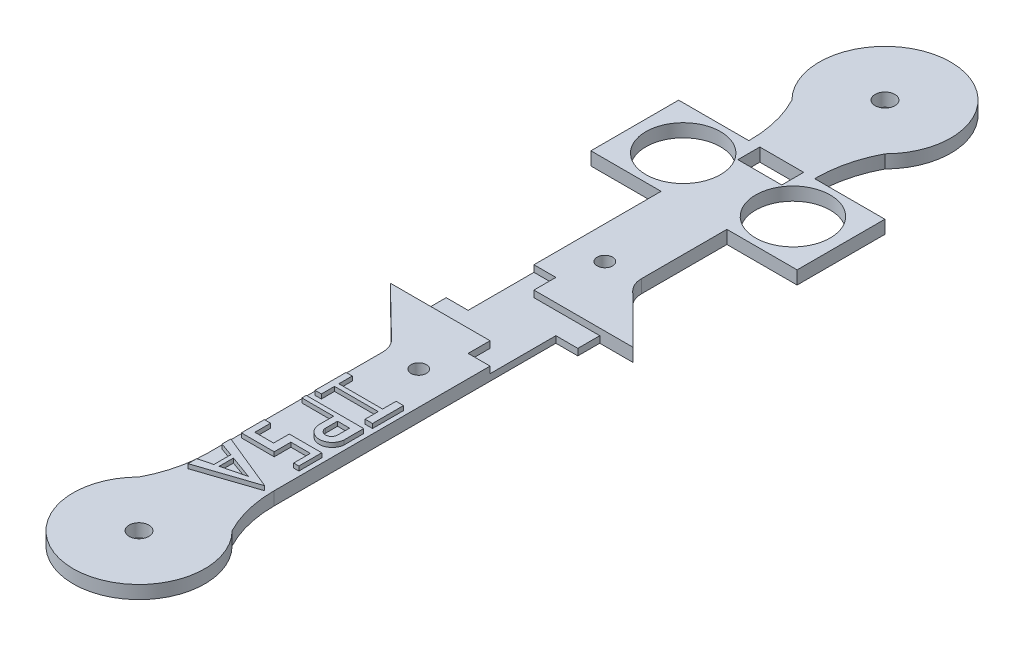
SolidWorks part; units mm, degrees
material "ABS"
ref_plane "Front Plane" through (0, 0, 0) normal (0, 0, 1) x (1, 0, 0)
ref_plane "Top Plane" through (0, 0, 0) normal (0, 1, 0) x (1, 0, 0)
ref_plane "Right Plane" through (0, 0, 0) normal (1, 0, 0) x (0, 0, -1)
sketch "Sketch1" plane through (0, 0, 0) normal (0, 1, 0) x (1, 0, 0)
  line L0 (-19.3064, 0) -> (26.0375, 0) construction
  line L3 (-7.451, -61.7809) -> (-7.451, 61.7809)
  line L4 (7.549, -61.7809) -> (7.549, 61.7809)
  arc A6 (10.6556, 74.3934) -> (-10.5576, 74.3934) centre (0.049, 85) ccw
  arc A12 (-7.451, 61.7809) -> (-10.5576, 74.3934) centre (-34.607, 61.7809) ccw
  arc A13 (7.549, 61.7809) -> (10.6556, 74.3934) centre (34.705, 61.7809) cw
  circle A14 centre (0.049, 85) radius 2
  circle A27 centre (0, 20) radius 1.5
  circle A30 centre (0.049, -85) radius 2
  arc A33 (7.549, -61.7809) -> (10.6556, -74.3934) centre (34.705, -61.7809) ccw
  arc A34 (10.6556, -74.3934) -> (-10.5576, -74.3934) centre (0.049, -85) cw
  arc A35 (-7.451, -61.7809) -> (-10.5576, -74.3934) centre (-34.607, -61.7809) cw
  circle A36 centre (0, -20) radius 1.5
  point P41 (7.549, 0)
  point P42 (-7.451, 0)
  dimension "D2" = 4
  dimension "D7" = 4
  dimension "D9" = 3
  dimension "D8" = 15
  dimension "D12" = 20
  dimension "D13" = 20
  dimension "D14" = 170
extrude "Boss-Extrude2" add sketch "Sketch1" along normal blind 3
sketch "Sketch3" plane through (0, 3, 0) normal (0, 1, 0) x (1, 0, 0)
  line L0 (-47.0006, 0) -> (46.456, 0) construction
  line L1 (7.549, -61.7809) -> (7.549, 61.7809) construction
  line L2 (-7.549, -7.5) -> (7.549, -7.5)
  line L3 (-7.549, -7.5) -> (-7.549, 7.5)
  line L4 (-7.549, 7.5) -> (7.549, 7.5)
  line L5 (7.549, -7.5) -> (7.549, 7.5)
  line L6 (-7.549, -7.5) -> (7.549, 7.5) construction
  line L7 (-7.549, 7.5) -> (7.549, -7.5) construction
  point P3 (0, 0)
  dimension "D1" = 15
extrude "Cut-Extrude9" cut sketch "Sketch3" against normal blind 1.5
sketch "Sketch4" plane through (0, 1.5, 0) normal (0, 1, 0) x (1, 0, 0)
  line L1 (-7.451, -7.5) -> (-20.167, -7.5)
  line L2 (-7.451, -7.5) -> (-7.3802, -20)
  line L3 (-7.3802, -20) -> (-20.167, -7.5)
  line L9 (-20.167, -20) -> (-7.3802, -20)
  line L10 (-20.167, -20) -> (-20.167, -7.5)
  line L13 (-7.451, -7.5) -> (-20.167, -7.5)
  line L14 (-20.167, -7.5) -> (-7.451, -7.5)
  line L17 (-20.167, -20) -> (-13.8196, -13.7051) construction
  line L19 (7.549, -7.5) -> (7.549, 7.5) construction
  line L20 (7.549, 7.5) -> (-7.451, 7.5) construction
  line L21 (7.549, 7.5) -> (20.167, 7.5)
  line L24 (-7.5626, -7.5) -> (7.5626, 7.5) construction
  line L25 (7.549, 7.5) -> (7.549, 20)
  line L26 (7.549, 20) -> (20.167, 7.5)
  point P0 (0, 0)
  point P7 (0, 0)
extrude "Boss-Extrude7" add sketch "Sketch4" along normal mid plane 3 contours L3 L2 L1 | L26 L25 L21
sketch "Sketch5" plane through (0, 3, 0) normal (0, 1, 0) x (1, 0, 0)
  line L0 (7.549, 2.5) -> (7.549, 7.5)
  line L10 (-20.167, -7.5) -> (7.549, -7.5) construction
  line L19 (7.549, -61.7809) -> (7.549, -7.5) construction
  line L20 (20.167, 7.5) -> (-7.451, 7.5) construction
  line L21 (7.549, 7.5) -> (2.549, 7.5)
  line L22 (-7.451, -2.5) -> (-7.451, -7.5)
  line L23 (-7.451, -7.5) -> (7.549, -7.5)
  line L25 (7.549, -7.5) -> (5.2347, -7.5)
  line L33 (-7.451, -7.5) -> (-2.451, -7.5)
  line L37 (7.549, 7.5) -> (2.549, 7.5)
  line L41 (-7.451, -7.5) -> (-2.451, -7.5)
  line L42 (-7.451, -7.5) -> (-7.451, -2.5)
  line L43 (-7.451, -2.5) -> (-2.451, -2.5)
  line L44 (-2.451, -7.5) -> (-2.451, -2.5)
  line L45 (2.549, 7.5) -> (7.549, 7.5)
  line L46 (2.549, 7.5) -> (2.549, 2.5)
  line L47 (2.549, 2.5) -> (7.549, 2.5)
  line L48 (7.549, 7.5) -> (7.549, 2.5)
  line L50 (-7.451, -7.5) -> (-7.451, -2.5)
  line L53 (-7.451, -2.5) -> (-12.4461, -2.5)
  line L54 (-7.451, -2.5) -> (-7.451, -7.5)
  line L55 (-7.451, -7.5) -> (-12.4461, -7.5)
  line L56 (-12.4461, -2.5) -> (-12.4461, -7.5)
  line L57 (7.549, 7.5) -> (12.549, 7.5)
  line L58 (7.549, 7.5) -> (7.549, 2.5)
  line L59 (7.549, 2.5) -> (12.549, 2.5)
  line L60 (12.549, 7.5) -> (12.549, 2.5)
  dimension "D1" = 5
  dimension "D5" = 5
  dimension "D6" = 5
sketch "Sketch7" plane through (0, 3, 0) normal (0, 1, 0) x (1, 0, 0)
  line L0 (-7.451, -19.9308) -> (-8.8812, -18.5327)
  line L1 (7.549, 20) -> (7.549, 22)
  line L5 (-34.7561, 0) -> (40.5625, 0) construction
  line L6 (7.549, 20) -> (7.549, 61.7809) construction
  line L8 (7.549, 20) -> (20.167, 7.5) construction
  line L9 (8.9698, 18.5924) -> (7.549, 20)
  line L10 (-7.451, -19.9308) -> (-20.167, -7.5) construction
  line L11 (-7.451, -19.9308) -> (-7.451, -21.9308)
  line L12 (-7.451, -19.9308) -> (-7.451, -61.7809) construction
  arc A0 (-7.451, -21.9308) -> (-8.8812, -18.5327) centre (-12.203, -21.9308) ccw
  arc A1 (7.549, 22) -> (8.9698, 18.5924) centre (12.3455, 22) ccw
  dimension "D1" = 2
  dimension "D2" = 2
  dimension "D3" = 2
  dimension "D4" = 2
extrude "Boss-Extrude9" add sketch "Sketch7" against normal blind 3
sketch "Sketch11" plane through (0, 3, 0) normal (0, 1, 0) x (1, 0, 0)
  line L1 (-7.451, 7.5) -> (-2.451, 7.5)
  line L2 (-7.451, 7.5) -> (-7.451, 12.5)
  line L3 (-7.451, 12.5) -> (-2.451, 12.5)
  line L4 (-2.451, 7.5) -> (-2.451, 12.5)
  line L5 (7.549, -7.5) -> (2.549, -7.5)
  line L6 (7.549, -7.5) -> (7.549, -12.5)
  line L7 (7.549, -12.5) -> (2.549, -12.5)
  line L8 (2.549, -7.5) -> (2.549, -12.5)
  dimension "D1" = 5
  dimension "D2" = 5
  dimension "D3" = 5
  dimension "D4" = 5
extrude "Cut-Extrude16" cut sketch "Sketch11" against normal blind 1.5
sketch "Sketch12" plane through (0, 1.5, 0) normal (0, 1, 0) x (1, 0, 0)
  line L0 (7.549, 7.5) -> (-2.451, 7.5) construction
  line L1 (-7.451, -7.5) -> (-12.451, -7.5)
  line L2 (-7.451, -7.5) -> (-7.451, -2.5)
  line L3 (-7.451, -2.5) -> (-12.451, -2.5)
  line L4 (-12.451, -7.5) -> (-12.451, -2.5)
  line L5 (7.549, 7.5) -> (12.549, 7.5)
  line L6 (7.549, 7.5) -> (7.549, 2.5)
  line L7 (7.549, 2.5) -> (12.549, 2.5)
  line L8 (12.549, 7.5) -> (12.549, 2.5)
  line L9 (7.549, -12.5) -> (7.549, 7.5) construction
  dimension "D1" = 5
  dimension "D2" = 5
  dimension "D3" = 5
  dimension "D4" = 5
extrude "Boss-Extrude16" add sketch "Sketch12" against normal blind 1.5
sketch "Sketch15" plane through (0, 3, 0) normal (0, 1, 0) x (1, 0, 0)
  circle A0 centre (0, -20) radius 1.5
  circle A1 centre (0, 20) radius 1.5
extrude "Boss-Extrude17" add sketch "Sketch15" against normal blind 3
sketch "Sketch16" plane through (0, 3, 0) normal (0, 1, 0) x (1, 0, 0)
  line L1 (24.0526, 0) -> (-32.7174, 0) construction
  circle A0 centre (0, -21.2132) radius 1.5
  circle A1 centre (0, 21.2132) radius 1.5
  dimension "D1" = 3
  dimension "D2" = 3
  dimension "D3" = 42.4264
extrude "Cut-Extrude17" cut sketch "Sketch16" against normal through all
sketch "Sketch18" plane through (0, 3, 0) normal (0, 1, 0) x (1, 0, 0)
  line L1 (7.549, 31.647) -> (-7.451, 31.647)
  line L6 (-7.451, 31.647) -> (-7.451, 46.246)
  line L7 (0.049, 85) -> (0.049, 61.4736) construction
  line L10 (7.549, 31.647) -> (3.8438, 41.4736)
  line L12 (22.5624, 61.4736) -> (-22.4376, 61.4736)
  line L14 (22.5624, 41.4736) -> (-22.4376, 41.4736)
  line L17 (0, 0) -> (0.049, 85) construction
  line L18 (0.049, 41.4736) -> (0.049, 13.3789) construction
  line L19 (-22.4376, 41.4736) -> (-23.4509, 41.4736)
  line L20 (-23.4509, 41.4736) -> (-23.4509, 61.4736)
  line L21 (-23.4509, 61.4736) -> (-22.4376, 61.4736)
  line L22 (23.5491, 51.4736) -> (23.5491, 61.4736)
  line L23 (23.5491, 61.4736) -> (22.5624, 61.4736)
  line L24 (23.5491, 51.4736) -> (23.5491, 41.4736)
  line L25 (23.5491, 41.4736) -> (22.5624, 41.4736)
  line L26 (5.049, 61.4736) -> (5.049, 56.4736)
  line L27 (5.049, 56.4736) -> (-4.951, 56.4736)
  line L28 (7.549, 46.246) -> (7.549, 31.647)
  line L29 (4.0297, 51.5366) -> (12.5297, 51.5366) construction
  line L30 (23.5491, 61.4736) -> (-23.4509, 41.4736) construction
  line L31 (-3.9703, 51.5366) -> (-12.4703, 51.5366) construction
  line L32 (4.0297, 51.5366) -> (-3.9703, 51.5366) construction
  line L33 (0.049, 61.4736) -> (5.049, 61.4736)
  line L34 (0.049, 61.4736) -> (-4.951, 61.4736)
  line L35 (-4.951, 56.4736) -> (-4.951, 61.4736)
  line L36 (-4.951, 56.4736) -> (-4.4703, 56.4736)
  circle A0 centre (12.5297, 51.5366) radius 8.5
  circle A1 centre (-12.4703, 51.5366) radius 8.5
  point P6 (0.049, 51.5375)
  line M16 (7.549, 22) -> (7.549, 61.7809)
  line M20 (-7.451, 61.7809) -> (-7.451, 12.5)
  dimension "D5" = 8.5
  dimension "D6" = 5
  dimension "D1" = 4
  dimension "D2" = 20
  dimension "D3" = 4
  dimension "D4" = 8.5
  dimension "D7" = 5
sketch "Sketch23" plane through (0, 3, 0) normal (0, 1, 0) x (1, 0, 0)
  line L0 (4.7905, -31.1563) -> (4.7905, -34.2247)
  line L1 (-7.451, -21.9308) -> (7.4854, -21.9308)
  line L2 (-7.451, -21.9308) -> (-7.451, -82.5219)
  line L3 (-7.451, -82.5219) -> (7.4854, -82.5219)
  line L4 (7.4854, -21.9308) -> (7.4854, -82.5219)
  line L5 (-6.6102, -81.3428) -> (6.483, -81.3428)
  line L6 (-6.6102, -81.3428) -> (-6.6102, -31.1563)
  line L7 (-6.6102, -31.1563) -> (6.483, -31.1563)
  line L8 (6.483, -81.3428) -> (6.483, -31.1563)
  line L9 (4.7905, -34.2247) -> (-5.1932, -34.2247)
  line L10 (-5.1932, -34.2247) -> (-5.1932, -31.1563)
  line L11 (6.483, -38.2247) -> (4.7905, -38.2247)
  line L12 (4.7905, -35.2247) -> (4.7905, -38.2247)
  line L13 (4.7905, -35.2247) -> (-5.172, -35.2247)
  line L14 (-5.172, -35.2247) -> (-5.172, -38.2247)
  line L15 (-5.172, -38.2247) -> (-6.6102, -38.2247)
  line L16 (-6.6102, -40.2287) -> (0.614, -40.2287)
  line L17 (0.614, -40.2287) -> (6.483, -40.2287)
  line L18 (6.483, -40.2287) -> (6.483, -46.7946)
  line L19 (0.614, -41.2287) -> (0.614, -44.4723)
  line L20 (-6.6102, -41.2287) -> (0.614, -41.2287)
  line L21 (4.7905, -41.7559) -> (2.0489, -41.7559)
  line L22 (2.0489, -41.7559) -> (2.0489, -44.4723)
  line L23 (4.7905, -44.4723) -> (4.7905, -41.7559)
  line L24 (6.483, -54.1856) -> (6.483, -49.4842)
  line L25 (-6.6102, -49.787) -> (-5.1932, -49.787)
  line L26 (5.304, -55.0101) -> (6.483, -55.0101)
  line L27 (0.8671, -55.0101) -> (-6.6102, -55.0101)
  line L28 (-6.6102, -55.0101) -> (-6.6102, -48.3283)
  line L29 (-6.6102, -57.4179) -> (-6.6102, -59.4179)
  line L30 (-5.1932, -49.787) -> (-5.1932, -53.3578)
  line L31 (-5.1932, -53.3578) -> (-0.919, -53.3578)
  line L32 (-0.919, -53.3578) -> (-0.919, -49.787)
  line L33 (-0.919, -49.787) -> (3.6751, -49.787)
  line L34 (3.6751, -49.787) -> (5.304, -49.787)
  line L35 (5.304, -51.2093) -> (5.304, -55.0101)
  line L36 (-6.6102, -57.4179) -> (6.483, -62.7841)
  line L37 (0.8671, -51.2093) -> (5.304, -51.2093)
  line L38 (0.8671, -51.2093) -> (0.8671, -55.0101)
  line L39 (5.304, -49.787) -> (6.483, -49.787)
  line L40 (-6.6102, -67.1769) -> (-6.6102, -65.1769)
  line L41 (6.483, -62.7841) -> (-6.6102, -67.1769)
  line L42 (-6.6102, -67.1769) -> (-6.6102, -64.1456)
  line L43 (-6.6102, -59.4179) -> (-3.4958, -60.5424)
  line L44 (-6.6102, -65.1769) -> (-3.4958, -64.3922)
  line L45 (-2.5421, -60.8868) -> (-2.5421, -64.1519)
  line L46 (-3.4958, -60.5424) -> (-3.4958, -64.3922)
  line L47 (-2.5421, -60.8868) -> (2.7839, -62.8099)
  line L48 (-2.5421, -64.1519) -> (2.7839, -62.8099)
  arc A2 (0.614, -44.4723) -> (6.483, -44.7743) centre (3.5563, -44.4723) ccw
  arc A3 (2.0489, -44.4723) -> (4.7905, -44.4723) centre (3.4197, -44.4723) ccw
  point P7 (-0.0636, -56.3282)
  dimension "D1" = 3.0684
  dimension "D2" = 3
  dimension "D3" = 3
  dimension "D4" = 1
  dimension "D5" = 1
  dimension "D6" = 2
  dimension "D7" = 2
extrude "Boss-Extrude23" add sketch "Sketch23" along normal blind 1 contours L15 L14 L13 L12 L11 L8 L7 L0 L9 L10 L6 | L19 A2 L18 L17 L16 L6 L20 A3 L22 L21 L23 | L39 L34 L33 L32 L31 L30 L25 L6 L27 L38 L37 L35 L26 L8 | L43 L46 L44 L6 L41 L36 L48 L45 L47
extrude "Boss-Extrude27" add sketch "Sketch18" against normal blind 3 contours A0 L14 L25 L24 L22 L23 L12 M16 | A1 L12 L21 L20 L19 L14 L6 M20
sketch "Sketch27" plane through (0, 3, 0) normal (0, 1, 0) x (1, 0, 0)
  line L0 (7.549, 61.4736) -> (-7.451, 61.4736)
  line L1 (-7.451, 61.4736) -> (-23.4509, 61.4736) construction
  line L2 (0.049, 61.4736) -> (0.049, 41.4736)
  line L3 (0.049, 61.4736) -> (5.049, 61.4736)
  line L4 (0.049, 61.4736) -> (-4.951, 61.4736)
  line L5 (5.049, 61.4736) -> (5.049, 56.4736)
  line L6 (5.049, 56.4736) -> (-4.951, 56.4736)
  line L7 (-4.951, 56.4736) -> (-4.951, 61.4736)
  circle A0 centre (12.5297, 51.5366) radius 8.5
  circle A1 centre (-12.4703, 51.5366) radius 8.5
  line M27 (7.549, 44.6488) -> (7.549, 58.4245)
  line M29 (-7.451, 58.3964) -> (-7.451, 44.6768)
  dimension "D1" = 5
  dimension "D2" = 5
  dimension "D3" = 5
extrude "Cut-Extrude20" cut sketch "Sketch27" against normal blind 3 contours A0 M27 | A1 M29 | L6 L5 L0 L2 | L7 L6 L2 L0
sketch "Sketch28" plane through (0, 3, 0) normal (0, 1, 0) x (1, 0, 0)
  circle A0 centre (0.049, 85) radius 2.25
  circle A1 centre (0.049, -85) radius 2.25
  dimension "D1" = 4.5
  dimension "D2" = 4.5
extrude "Cut-Extrude22" cut sketch "Sketch28" against normal through all contours A1 | A0
sketch "Sketch29" plane through (0, 3, 0) normal (0, 1, 0) x (1, 0, 0)
  circle A0 centre (0, 21.2132) radius 1.75
  circle A1 centre (0, -21.2132) radius 1.75
  dimension "D1" = 3.5
  dimension "D2" = 3.5
extrude "Cut-Extrude23" cut sketch "Sketch29" against normal blind 10
